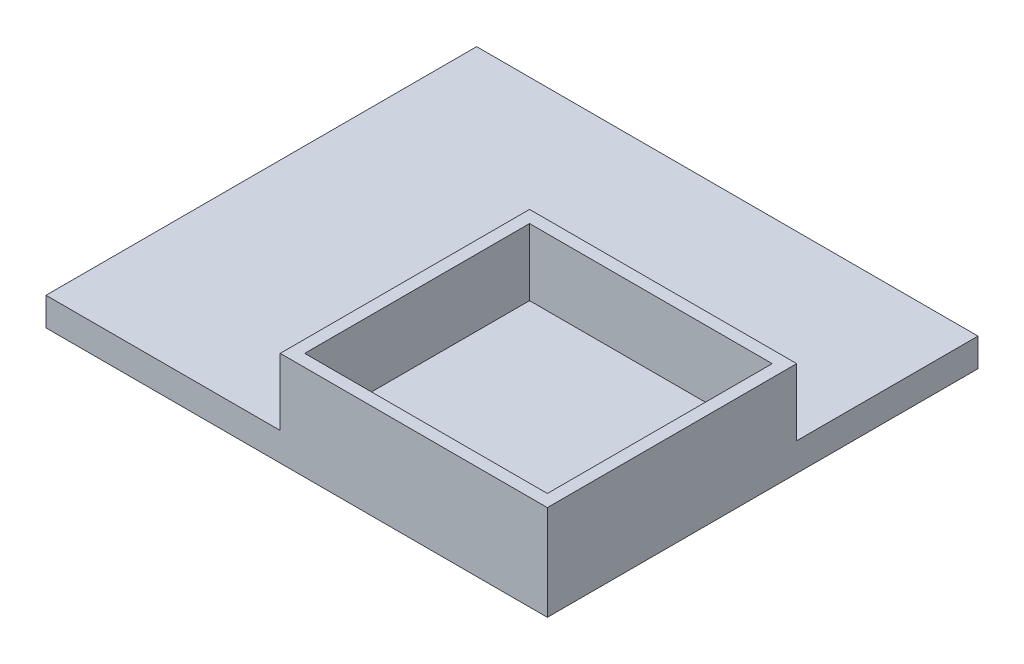
SolidWorks part; units mm, degrees
ref_plane "Front Plane" through (0, 0, 0) normal (0, 0, 1) x (1, 0, 0)
ref_plane "Top Plane" through (0, 0, 0) normal (0, 1, 0) x (1, 0, 0)
ref_plane "Right Plane" through (0, 0, 0) normal (1, 0, 0) x (0, 0, -1)
sketch "Sketch1" plane through (0, 0, 0) normal (0, 1, 0) x (1, 0, 0)
  line L1 (-56.3, 20.36) -> (56.3, 20.36)
  line L2 (-56.3, 20.36) -> (-56.3, -20.36)
  line L3 (-56.3, -20.36) -> (56.3, -20.36)
  line L4 (56.3, 20.36) -> (56.3, -20.36)
  line L5 (-56.3, 20.36) -> (56.3, -20.36) construction
  line L6 (-56.3, -20.36) -> (56.3, 20.36) construction
  point P0 (0, 0)
  dimension "D1" = 112.6
  dimension "D2" = 40.72
extrude "Boss-Extrude1" add sketch "Sketch1" along normal blind 6.35
sketch "Sketch2" plane through (0, 0, 20.36) normal (0, 0, 1) x (1, 0, 0)
  line L1 (-56.3, 6.35) -> (56.3, 6.35)
  line L2 (-56.3, 6.35) -> (-56.3, 0)
  line L3 (-56.3, 0) -> (56.3, 0)
  line L4 (56.3, 6.35) -> (56.3, 0)
extrude "Boss-Extrude2" add sketch "Sketch2" along normal blind 56
sketch "Sketch3" plane through (0, 6.35, 0) normal (0, 1, 0) x (1, 0, 0)
  line L0 (56.3, -76.36) -> (-3.7, -76.36)
  line L1 (56.3, -76.36) -> (-56.3, -76.36) construction
  line L2 (-3.7, -76.36) -> (-3.7, -20.36)
  line L3 (-3.7, -20.36) -> (56.3, -20.36)
  line L4 (56.3, -76.36) -> (56.3, 20.36) construction
  line L5 (56.3, -20.36) -> (56.3, -76.36)
  line L6 (-0.95, -23.11) -> (53.55, -23.11)
  line L7 (53.55, -23.11) -> (53.55, -73.61)
  line L8 (53.55, -73.61) -> (-0.95, -73.61)
  line L9 (-0.95, -73.61) -> (-0.95, -23.11)
  dimension "D1" = 2.75
  dimension "D2" = 2.75
  dimension "D3" = 2.75
  dimension "D4" = 2.75
  dimension "D5" = 54.5
  dimension "D6" = 50.5
extrude "Boss-Extrude3" add sketch "Sketch3" along normal blind 15
